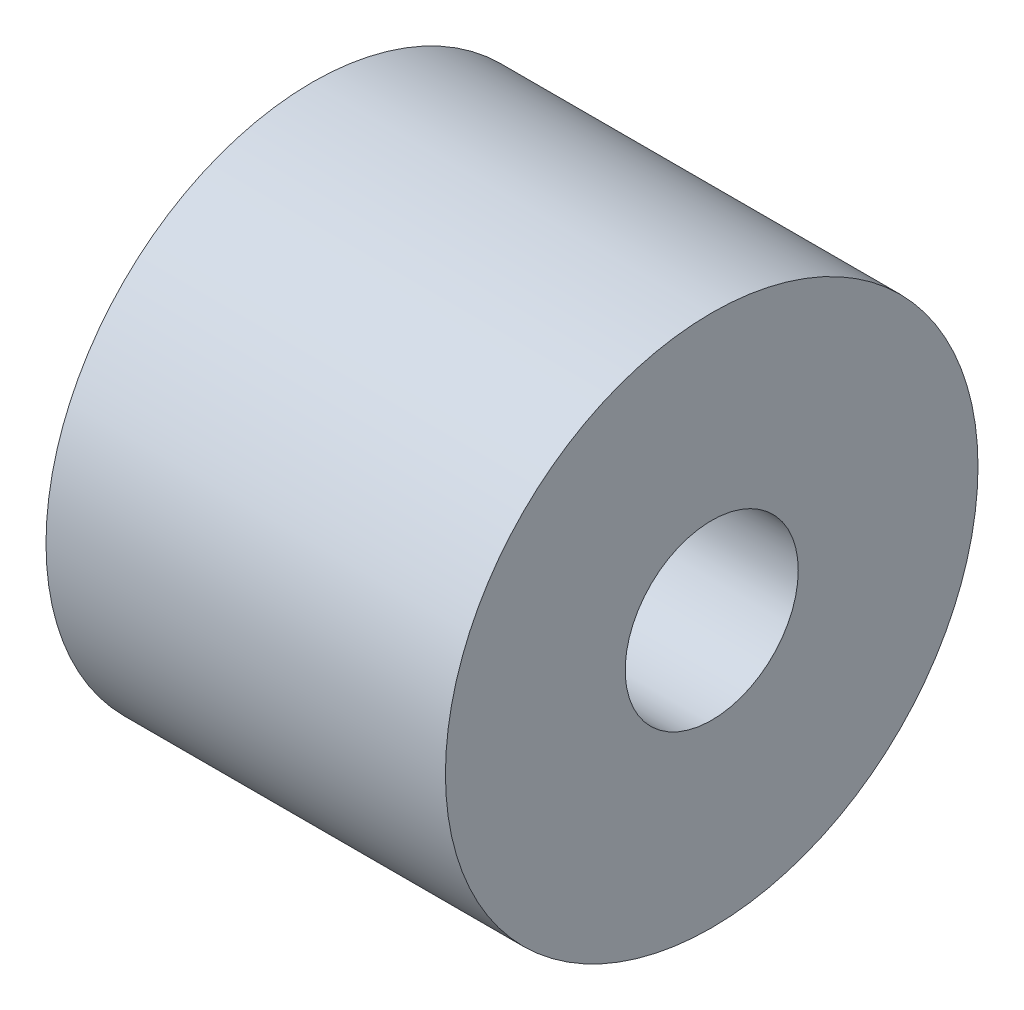
SolidWorks part; units mm, degrees
ref_plane "Front Plane" through (0, 0, 0) normal (0, 0, 1) x (1, 0, 0)
ref_plane "Top Plane" through (0, 0, 0) normal (0, 1, 0) x (1, 0, 0)
ref_plane "Right Plane" through (0, 0, 0) normal (1, 0, 0) x (0, 0, -1)
sketch "Sketch1" plane through (0, 0, 0) normal (1, 0, 0) x (0, 0, -1)
  circle A0 centre (0, 0) radius 10
  circle A1 centre (0, 0) radius 3.25
  dimension "D1" = 6.5
  dimension "D2" = 20
extrude "Boss-Extrude1" add sketch "Sketch1" along normal blind 15
